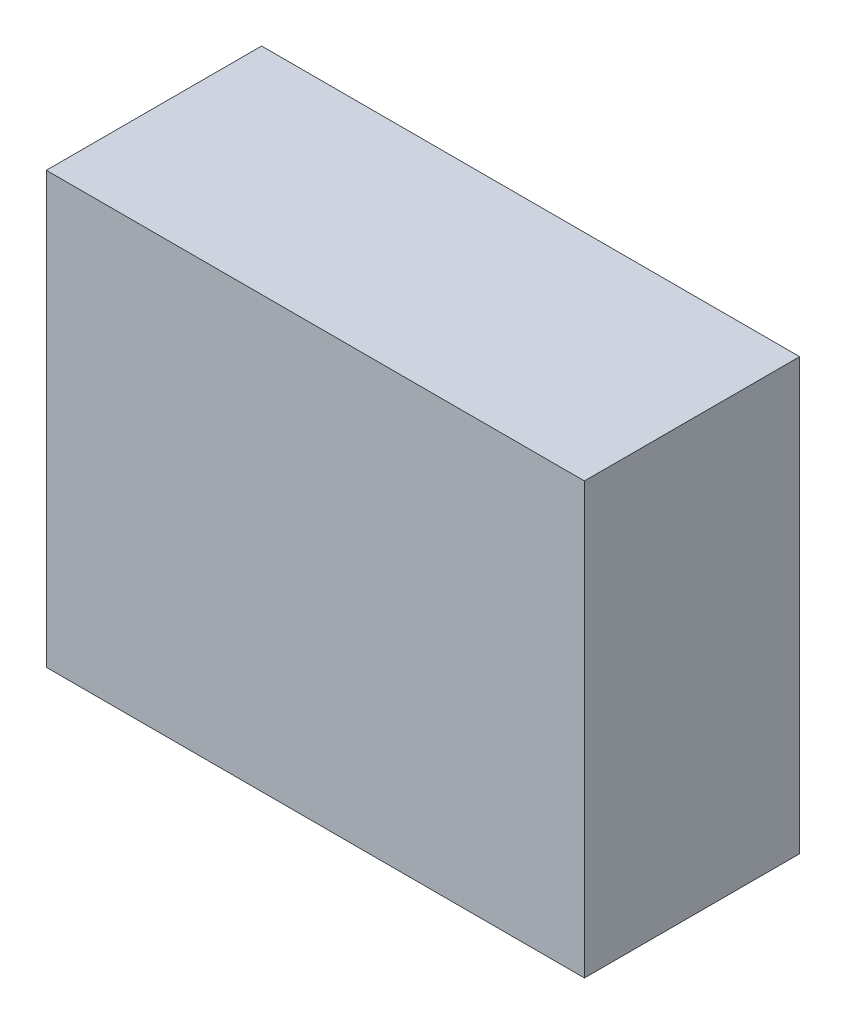
SolidWorks part; units mm, degrees
ref_plane "정면" through (0, 0, 0) normal (0, 0, 1) x (1, 0, 0)
ref_plane "윗면" through (0, 0, 0) normal (0, 1, 0) x (1, 0, 0)
ref_plane "우측면" through (0, 0, 0) normal (1, 0, 0) x (0, 0, -1)
sketch "스케치1" plane through (0, 0, 0) normal (0, 1, 0) x (1, 0, 0)
  line L1 (-25, -10) -> (25, -10)
  line L2 (-25, -10) -> (-25, 10)
  line L3 (-25, 10) -> (25, 10)
  line L4 (25, -10) -> (25, 10)
  line L5 (-25, -10) -> (25, 10) construction
  line L6 (-25, 10) -> (25, -10) construction
  point P0 (0, 0)
extrude "보스-돌출1" add sketch "스케치1" along normal blind 40
